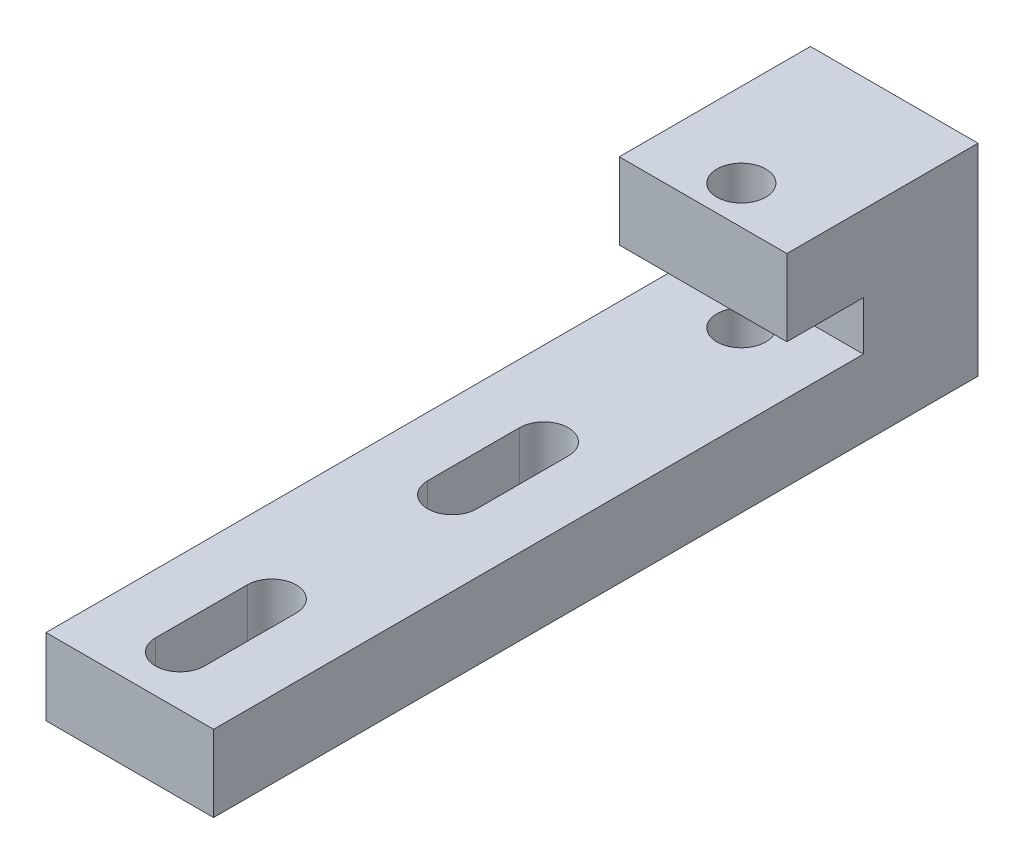
SolidWorks part; units mm, degrees
ref_plane "Front Plane" through (0, 0, 0) normal (0, 0, 1) x (1, 0, 0)
ref_plane "Top Plane" through (0, 0, 0) normal (0, 1, 0) x (1, 0, 0)
ref_plane "Right Plane" through (0, 0, 0) normal (1, 0, 0) x (0, 0, -1)
sketch "Sketch1" plane through (0, 0, 0) normal (0, 1, 0) x (1, 0, 0)
  line L0 (5.4811, 45) -> (5.4811, 0) construction
  line L1 (0, 0) -> (10.9622, 0)
  line L2 (0, 0) -> (0, 45)
  line L3 (0, 45) -> (10.9622, 45)
  line L4 (10.9622, 0) -> (10.9622, 45)
  line L5 (5.4811, 27.0855) -> (5.4811, 21.0855) construction
  line L6 (7.0811, 27.0855) -> (7.0811, 21.0855)
  line L7 (3.8811, 27.0855) -> (3.8811, 21.0855)
  line L8 (5.4811, 3.2855) -> (5.4811, 9.2855) construction
  line L9 (3.8811, 3.2855) -> (3.8811, 9.2855)
  line L10 (7.0811, 3.2855) -> (7.0811, 9.2855)
  arc A0 (7.0811, 27.0855) -> (3.8811, 27.0855) centre (5.4811, 27.0855) ccw
  arc A1 (3.8811, 21.0855) -> (7.0811, 21.0855) centre (5.4811, 21.0855) ccw
  arc A2 (3.8811, 3.2855) -> (7.0811, 3.2855) centre (5.4811, 3.2855) ccw
  arc A3 (7.0811, 9.2855) -> (3.8811, 9.2855) centre (5.4811, 9.2855) ccw
  circle A4 centre (5.4811, 40) radius 1.25
  point P9 (5.4811, 24.0855)
  point P15 (5.4811, 6.2855)
  point P21 (5.4811, 19.4855)
  point P22 (5.4811, 1.6855)
  dimension "D5" = 5
  dimension "D6" = 2.5
  dimension "D7" = 1.6
  dimension "D8" = 1.6
  dimension "D1" = 17.8
  dimension "D2" = 45
  dimension "D3" = 6
  dimension "D4" = 6
extrude "Boss-Extrude1" add sketch "Sketch1" along normal blind 5
sketch "Sketch2" plane through (0, 5, 0) normal (0, 1, 0) x (1, 0, 0)
  line L0 (10.9622, 0) -> (10.9622, 45) construction
  line L1 (0, 45) -> (10.9622, 45)
  line L2 (0, 45) -> (0, 42.5)
  line L3 (0, 42.5) -> (10.9622, 42.5)
  line L4 (10.9622, 45) -> (10.9622, 42.5)
  dimension "D1" = 2.5
extrude "Boss-Extrude2" add sketch "Sketch2" along normal blind 8.2
sketch "Sketch3" plane through (0, 0, -42.5) normal (0, 0, 1) x (1, 0, 0)
  line L0 (10.9622, 13.2) -> (10.9622, 5) construction
  line L1 (0, 13.2) -> (10.9622, 13.2)
  line L2 (0, 13.2) -> (0, 8.2)
  line L3 (0, 8.2) -> (10.9622, 8.2)
  line L4 (10.9622, 13.2) -> (10.9622, 8.2)
  dimension "D1" = 5
extrude "Boss-Extrude3" add sketch "Sketch3" along normal blind 5
sketch "Sketch4" plane through (0, 8.2, 0) normal (0, -1, 0) x (1, 0, 0)
  circle A0 centre (5.4811, -40) radius 1.6
  dimension "D1" = 3.2
extrude "Cut-Extrude1" cut sketch "Sketch4" against normal through all both and the other way through all
sketch "Sketch5" plane through (0, 0, -45) normal (0, 0, -1) x (-1, 0, 0)
  line L1 (-10.9622, 13.2) -> (0, 13.2)
  line L2 (-10.9622, 13.2) -> (-10.9622, 0)
  line L3 (-10.9622, 0) -> (0, 0)
  line L4 (0, 13.2) -> (0, 0)
extrude "Boss-Extrude4" add sketch "Sketch5" along normal blind 5
